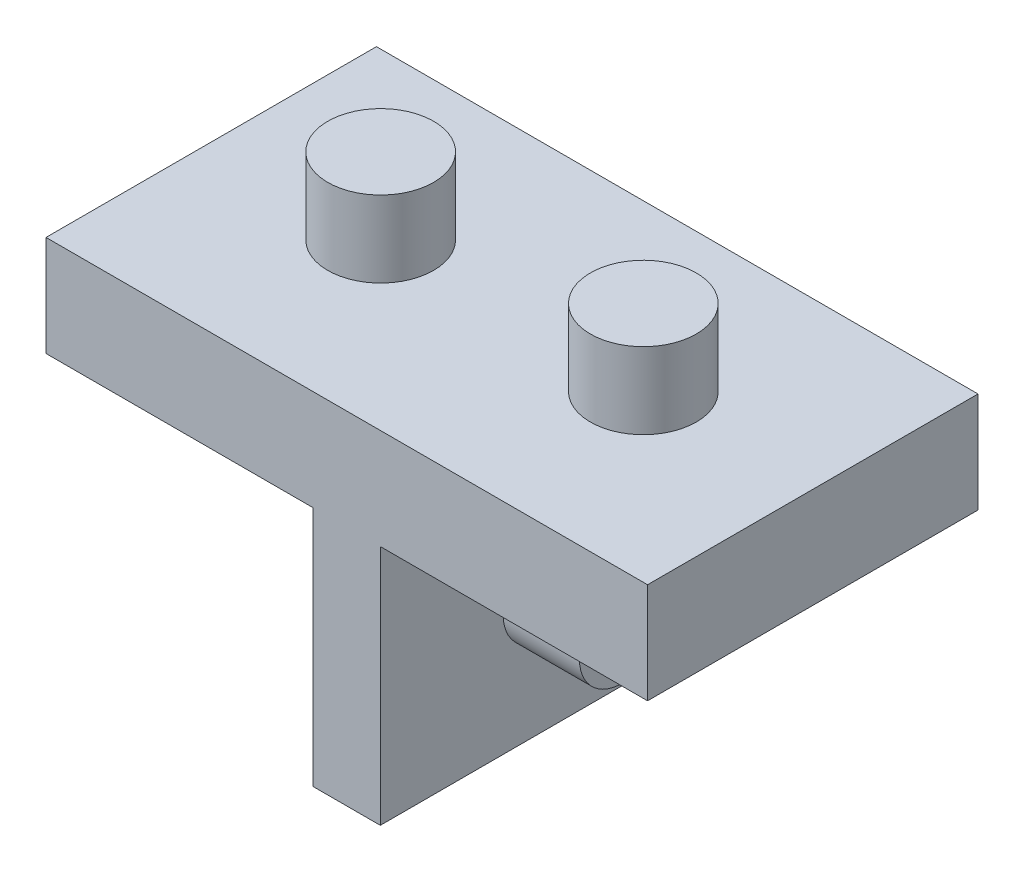
SolidWorks part; units mm, degrees
ref_plane "Alzado" through (0, 0, 0) normal (0, 0, 1) x (1, 0, 0)
ref_plane "Planta" through (0, 0, 0) normal (0, 1, 0) x (1, 0, 0)
ref_plane "Vista lateral" through (0, 0, 0) normal (1, 0, 0) x (0, 0, -1)
sketch "Croquis2" plane through (0, 0, 0) normal (0, 0, 1) x (1, 0, 0)
  line L0 (-21.3, 7.12) -> (-21.3, 0)
  line L1 (-21.3, 0) -> (-2.375, 0)
  line L2 (-2.375, 0) -> (-2.375, -17.1)
  line L3 (-2.375, -17.1) -> (2.375, -17.1)
  line L4 (2.375, -17.1) -> (2.375, 0)
  line L5 (2.375, 0) -> (21.3, 0)
  line L6 (21.3, 0) -> (21.3, 7.12)
  line L7 (21.3, 7.12) -> (-21.3, 7.12)
  dimension "D1" = 4.75
  dimension "D2" = 17.1
  dimension "D3" = 42.6
  dimension "D4" = 7.12
  dimension "D5" = 18.925
  dimension "D6" = 21.3
extrude "Saliente-Extruir1" add sketch "Croquis2" along normal mid plane 23.4
sketch "Croquis3" plane through (0, 7.12, 0) normal (0, 1, 0) x (1, 0, 0)
  line L0 (21.3, -11.7) -> (-21.3, -11.7) construction
  line L1 (-21.3, -11.7) -> (-21.3, 11.7) construction
  line L2 (21.3, -11.7) -> (21.3, 11.7) construction
  line L3 (21.3, 11.7) -> (-21.3, 11.7) construction
  circle A0 centre (-9.3, 0) radius 3.75
  circle A1 centre (9.3, 0) radius 3.75
  dimension "D1" = 7.5
  dimension "D2" = 11.7
  dimension "7.5" = 7.5
  dimension "D3" = 12
  dimension "D5" = 11.7
  dimension "D4" = 12
extrude "Saliente-Extruir2" add sketch "Croquis3" along normal blind 5.4
sketch "Croquis5" plane through (2.375, 0, 0) normal (1, 0, 0) x (0, 0, -1)
  line L0 (-11.7, -17.1) -> (11.7, -17.1) construction
  line L1 (11.7, -17.1) -> (11.7, 0) construction
  circle A0 centre (0, -8.55) radius 3
  dimension "D1" = 6
  dimension "D2" = 8.55
  dimension "D3" = 11.7
extrude "Saliente-Extruir3" add sketch "Croquis5" along normal blind 5.4
mirror "Simetría1" about plane through (0, 0, 0) normal (1, 0, 0) of "Saliente-Extruir3"
